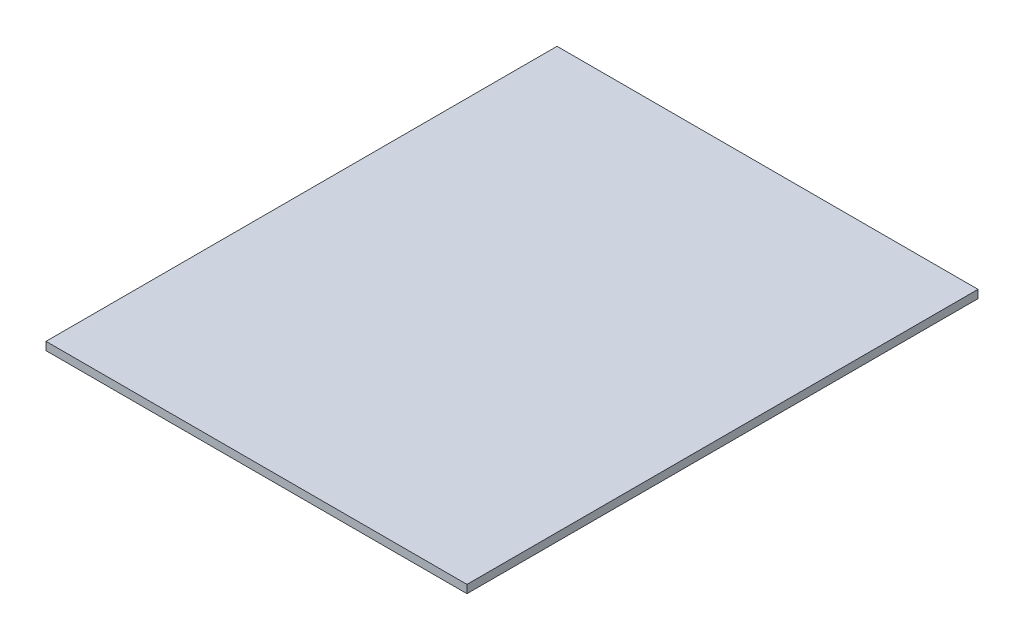
SolidWorks part; units mm, degrees
ref_plane "Front Plane" through (0, 0, 0) normal (0, 0, 1) x (1, 0, 0)
ref_plane "Top Plane" through (0, 0, 0) normal (0, 1, 0) x (1, 0, 0)
ref_plane "Right Plane" through (0, 0, 0) normal (1, 0, 0) x (0, 0, -1)
other "Configuration Table"
sketch "Sketch1" plane through (0, 0, 0) normal (0, 0, 1) x (1, 0, 0)
  line L1 (714, 1497) -> (1338, 1497)
  line L2 (714, 1497) -> (714, 1509)
  line L3 (714, 1509) -> (1338, 1509)
  line L4 (1338, 1497) -> (1338, 1509)
extrude "DET_raf_alt_1" add sketch "Sketch1" against normal blind 757.5 separate body
